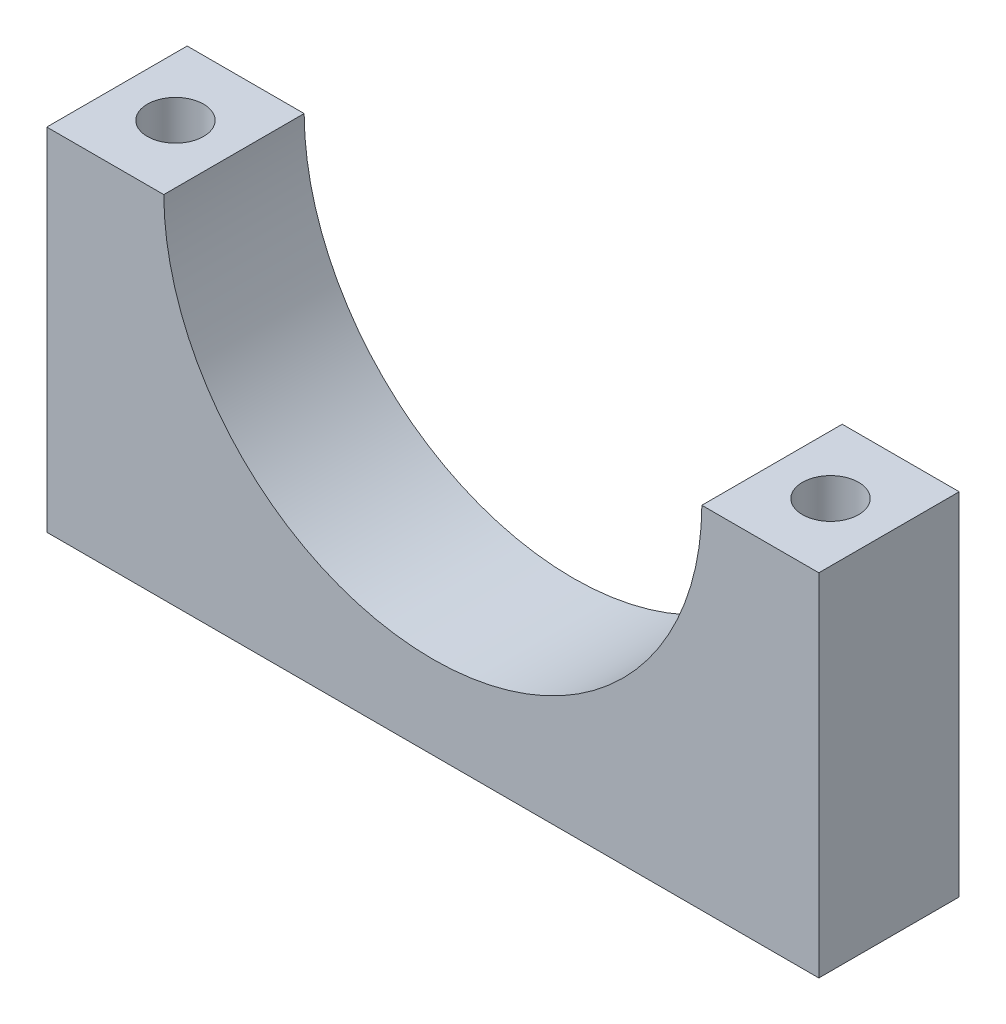
SolidWorks part; units mm, degrees
material "SKD11淬火HRC56-60"
ref_plane "前基準面" through (0, 0, 0) normal (0, 0, 1) x (1, 0, 0)
ref_plane "上基準面" through (0, 0, 0) normal (0, 1, 0) x (1, 0, 0)
ref_plane "右基準面" through (0, 0, 0) normal (1, 0, 0) x (0, 0, -1)
sketch "草图1" plane through (0, 0, 0) normal (0, 0, 1) x (1, 0, 0)
  line L1 (0, 0) -> (66, 0)
  line L2 (0, 0) -> (0, 30)
  line L3 (0, 30) -> (66, 30)
  line L4 (66, 0) -> (66, 30)
  dimension "D1" = 66
  dimension "D2" = 30
extrude "凸台-拉伸1" add sketch "草图1" along normal blind 12
sketch "草图2" plane through (0, 0, 12) normal (0, 0, 1) x (1, 0, 0)
  line L0 (33, 30) -> (33, 48.078) construction
  line L1 (66, 30) -> (0, 30) construction
  circle A0 centre (33, 30.1) radius 23
  dimension "D2" = 46
  dimension "D1" = 0.1
extrude "切除-拉伸1" cut sketch "草图2" against normal through all
hole_wizard "M4 六角凹头螺钉的柱形沉头孔1" positions "草图4" profile "草图3" counterbore size "M4" standard "ISO" end condition through all
sketch "草图4" plane through (0, 0, 0) normal (0, -1, 0) x (1, 0, 0)
  line L0 (66, 6) -> (0, 6) construction
  line L1 (66, 12) -> (66, 0) construction
  line L2 (0, 12) -> (0, 0) construction
  line L3 (33, 0) -> (33, 12) construction
  line L4 (0, 0) -> (66, 0) construction
  line L5 (0, 12) -> (66, 12) construction
  point P0 (61, 6)
  point P1 (5, 6)
  dimension "D1" = 5
sketch "草图3" plane through (61, 0, 6) normal (1, 0, 0) x (0, 0, -1)
  line L0 (0, 0) -> (0, 30)
  line L1 (0, 30) -> (2.4, 30)
  line L3 (2.4, 30) -> (2.4, 4)
  line L4 (2.4, 4) -> (4, 4)
  line L5 (4, 4) -> (4, 0)
  line L7 (4, 0) -> (0, 0)
  line L11 (0, -6.35) -> (0, 107.95) construction
  dimension "通孔孔直径" = 4.8
  dimension "通孔孔深度" = 30
  dimension "柱形沉头孔直径" = 8
  dimension "柱形沉头孔深度" = 4
